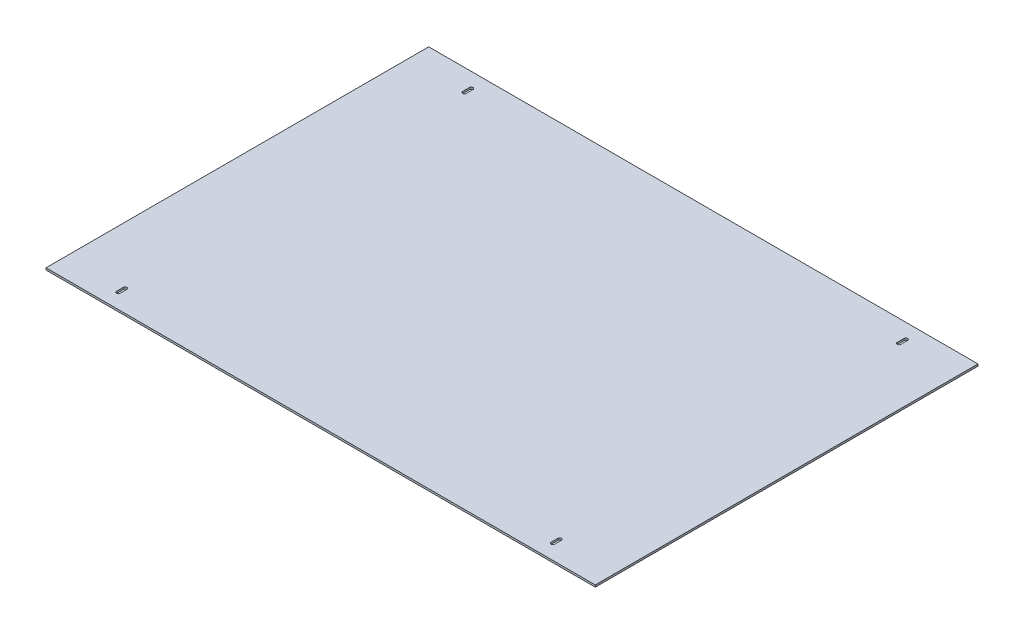
SolidWorks part; units mm, degrees
ref_plane "Front Plane" through (0, 0, 0) normal (0, 0, 1) x (1, 0, 0)
ref_plane "Top Plane" through (0, 0, 0) normal (0, 1, 0) x (1, 0, 0)
ref_plane "Right Plane" through (0, 0, 0) normal (1, 0, 0) x (0, 0, -1)
sketch "Sketch1" plane through (0, 0, 0) normal (0, 1, 0) x (1, 0, 0)
  line L1 (-353.1235, -246.0625) -> (353.1235, -246.0625)
  line L2 (-353.1235, -246.0625) -> (-353.1235, 246.0625)
  line L3 (-353.1235, 246.0625) -> (353.1235, 246.0625)
  line L4 (353.1235, -246.0625) -> (353.1235, 246.0625)
  line L5 (-353.1235, -246.0625) -> (353.1235, 246.0625) construction
  line L6 (-353.1235, 246.0625) -> (353.1235, -246.0625) construction
  point P1 (0, 0)
  dimension "D1" = 706.247
  dimension "D2" = 492.125
extrude "Boss-Extrude1" add sketch "Sketch1" along normal blind 2.54
sketch "Sketch2" plane through (0, 2.54, 0) normal (0, 1, 0) x (1, 0, 0)
  line L0 (353.1235, 0) -> (-353.1235, 0) construction
  line L1 (353.1235, -246.0625) -> (353.1235, 246.0625) construction
  line L2 (-353.1235, 246.0625) -> (-353.1235, -246.0625) construction
  line L3 (0, 246.0625) -> (0, -246.0625) construction
  line L4 (353.1235, 246.0625) -> (-353.1235, 246.0625) construction
  line L5 (-353.1235, -246.0625) -> (353.1235, -246.0625) construction
  line L6 (0, 246.0625) -> (0, 0) construction
  line L7 (-353.1235, 122.9995) -> (353.1235, 122.9995) construction
  line L8 (-353.1235, 122.9995) -> (0, 122.9995) construction
  line L9 (0, 122.9995) -> (353.1235, 122.9995) construction
  line L10 (334.0735, 122.9995) -> (334.0735, 246.0625) construction
  line L11 (334.0735, 218.1225) -> (334.0735, 227.0125) construction
  line L12 (331.8256, 218.1225) -> (331.8256, 227.0125)
  line L13 (336.3214, 218.1225) -> (336.3214, 227.0125)
  line L14 (334.0735, 227.0125) -> (334.0735, 246.0625) construction
  line L15 (-334.0735, 218.1225) -> (-334.0735, 227.0125) construction
  line L16 (-331.8256, 218.1225) -> (-331.8256, 227.0125)
  line L17 (-336.3214, 218.1225) -> (-336.3214, 227.0125)
  line L18 (334.0735, -218.1225) -> (334.0735, -227.0125) construction
  line L19 (331.8256, -218.1225) -> (331.8256, -227.0125)
  line L20 (336.3214, -218.1225) -> (336.3214, -227.0125)
  line L21 (-334.0735, -218.1225) -> (-334.0735, -227.0125) construction
  line L22 (-331.8256, -218.1225) -> (-331.8256, -227.0125)
  line L23 (-336.3214, -218.1225) -> (-336.3214, -227.0125)
  arc A0 (331.8256, 218.1225) -> (336.3214, 218.1225) centre (334.0735, 218.1225) ccw
  arc A1 (336.3214, 227.0125) -> (331.8256, 227.0125) centre (334.0735, 227.0125) ccw
  arc A2 (-331.8256, 218.1225) -> (-336.3214, 218.1225) centre (-334.0735, 218.1225) cw
  arc A3 (-336.3214, 227.0125) -> (-331.8256, 227.0125) centre (-334.0735, 227.0125) cw
  arc A4 (331.8256, -218.1225) -> (336.3214, -218.1225) centre (334.0735, -218.1225) cw
  arc A5 (336.3214, -227.0125) -> (331.8256, -227.0125) centre (334.0735, -227.0125) cw
  arc A6 (-331.8256, -218.1225) -> (-336.3214, -218.1225) centre (-334.0735, -218.1225) ccw
  arc A7 (-336.3214, -227.0125) -> (-331.8256, -227.0125) centre (-334.0735, -227.0125) ccw
  point P21 (334.0735, 222.5675)
  point P29 (-334.0735, 222.5675)
  point P36 (334.0735, -222.5675)
  point P43 (-334.0735, -222.5675)
  dimension "D1" = 4.4958
  dimension "D2" = 19.05
  dimension "D3" = 8.89
  dimension "D4" = 19.05
extrude "Cut-Extrude1" [suppressed] cut sketch "Sketch2" against normal blind 2.54
sketch "Sketch6" plane through (0, 2.54, 0) normal (0, 1, 0) x (1, 0, 0)
  line L0 (-279.4, 0) -> (279.4, 0) construction
  line L1 (279.4, 215.8746) -> (279.4, 246.0625) construction
  line L2 (353.1235, 246.0625) -> (-353.1235, 246.0625) construction
  line L3 (279.4, 218.1225) -> (279.4, 227.0125) construction
  line L4 (277.1521, 218.1225) -> (277.1521, 227.0125)
  line L5 (281.6479, 218.1225) -> (281.6479, 227.0125)
  line L6 (0, -246.0625) -> (0, 246.0625) construction
  line L7 (279.4, 222.5675) -> (279.4, -222.5675) construction
  line L8 (-279.4, 218.1225) -> (-279.4, 227.0125) construction
  line L9 (-277.1521, 218.1225) -> (-277.1521, 227.0125)
  line L10 (-281.6479, 218.1225) -> (-281.6479, 227.0125)
  line L11 (279.4, -218.1225) -> (279.4, -227.0125) construction
  line L12 (277.1521, -218.1225) -> (277.1521, -227.0125)
  line L13 (281.6479, -218.1225) -> (281.6479, -227.0125)
  line L14 (-279.4, -218.1225) -> (-279.4, -227.0125) construction
  line L15 (-277.1521, -218.1225) -> (-277.1521, -227.0125)
  line L16 (279.4, -215.8746) -> (279.4, -246.0625) construction
  line L17 (-281.6479, -218.1225) -> (-281.6479, -227.0125)
  line L18 (-279.4, -215.8746) -> (-279.4, -246.0625) construction
  line L19 (-279.4, 222.5675) -> (-279.4, -222.5675) construction
  line L20 (-279.4, 215.8746) -> (-279.4, 246.0625) construction
  arc A0 (277.1521, 218.1225) -> (281.6479, 218.1225) centre (279.4, 218.1225) ccw
  arc A1 (281.6479, 227.0125) -> (277.1521, 227.0125) centre (279.4, 227.0125) ccw
  arc A2 (277.1521, -218.1225) -> (281.6479, -218.1225) centre (279.4, -218.1225) cw
  arc A3 (281.6479, -227.0125) -> (277.1521, -227.0125) centre (279.4, -227.0125) cw
  arc A4 (-277.1521, 218.1225) -> (-281.6479, 218.1225) centre (-279.4, 218.1225) cw
  arc A5 (-281.6479, 227.0125) -> (-277.1521, 227.0125) centre (-279.4, 227.0125) cw
  arc A6 (-277.1521, -218.1225) -> (-281.6479, -218.1225) centre (-279.4, -218.1225) ccw
  arc A7 (-281.6479, -227.0125) -> (-277.1521, -227.0125) centre (-279.4, -227.0125) ccw
  point P8 (279.4, 222.5675)
  point P19 (-279.4, 222.5675)
  point P24 (279.4, -222.5675)
  point P33 (-279.4, -222.5675)
  point P36 (0, 0)
  dimension "D1" = 279.4
  dimension "D2" = 8.89
  dimension "D3" = 4.4958
  dimension "D4" = 23.495
extrude "Cut-Extrude2" cut sketch "Sketch6" against normal through all
sketch "Sketch7" [suppressed] plane through (0, 2.54, 0) normal (0, 1, 0) x (1, 0, 0)
  line L0 (-304.8, 0) -> (304.8, 0) construction
  line L1 (-304.8, 246.0625) -> (-304.8, -246.0625) construction
  line L2 (304.8, -246.0625) -> (304.8, 246.0625) construction
  line L3 (0, 246.0625) -> (0, -246.0625) construction
  line L4 (304.8, 246.0625) -> (-304.8, 246.0625) construction
  line L5 (-304.8, -246.0625) -> (304.8, -246.0625) construction
